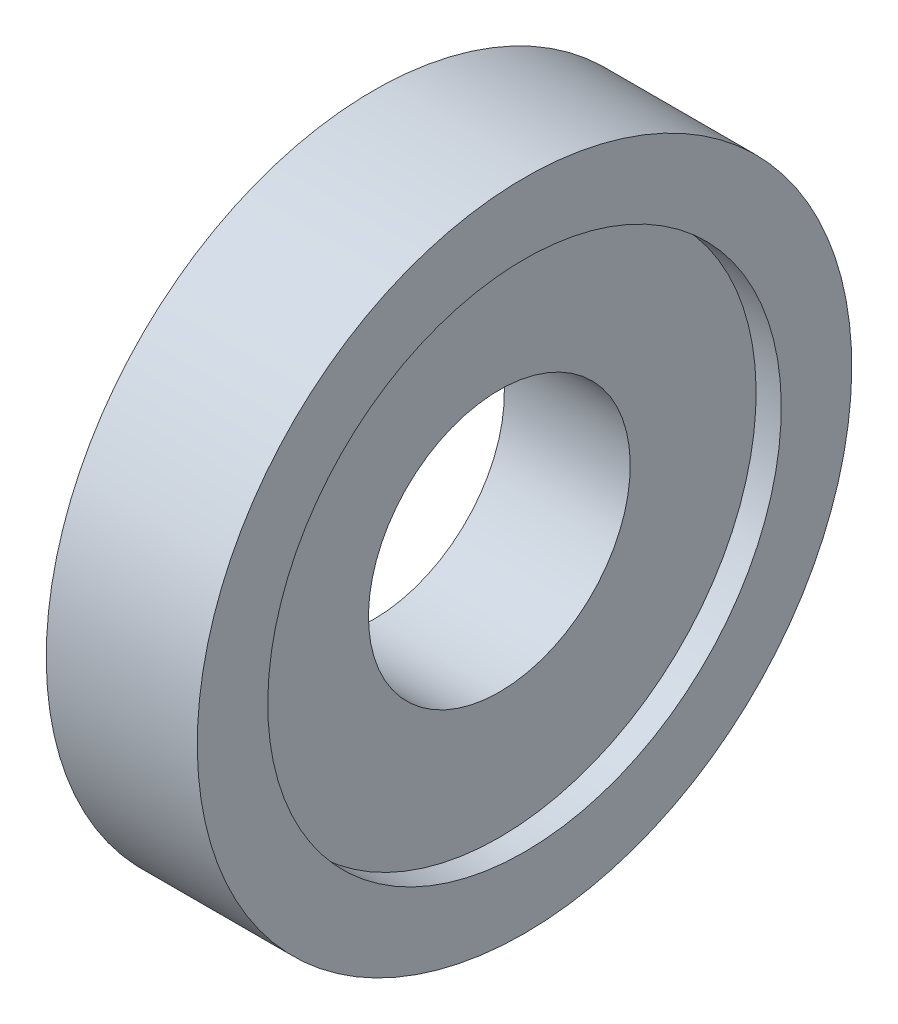
SolidWorks part; units mm, degrees
material "Vero PureWhite"
ref_plane "前视基准面" through (0, 0, 0) normal (0, 0, 1) x (1, 0, 0)
ref_plane "上视基准面" through (0, 0, 0) normal (0, 1, 0) x (1, 0, 0)
ref_plane "右视基准面" through (0, 0, 0) normal (1, 0, 0) x (0, 0, -1)
sketch "草图1" plane through (0, 0, 0) normal (0, 0, 1) x (1, 0, 0)
  line L0 (0, 0) -> (3.4841, 0) construction
  line L1 (0, 0) -> (0, 2.6) construction
  line L2 (0, 2.6) -> (0, 6.5)
  line L3 (0, 6.5) -> (3, 6.5)
  line L4 (3, 6.5) -> (3, 5.1)
  line L5 (3, 5.1) -> (2.5, 5.1)
  line L6 (2.5, 5.1) -> (2.5, 2.6)
  line L7 (2.5, 2.6) -> (0, 2.6)
  dimension "D1" = 13
  dimension "D2" = 5.2
  dimension "D3" = 10.2
  dimension "D4" = 3
  dimension "D5" = 0.5
revolve "旋转1" add sketch "草图1" angle 360 about L0
